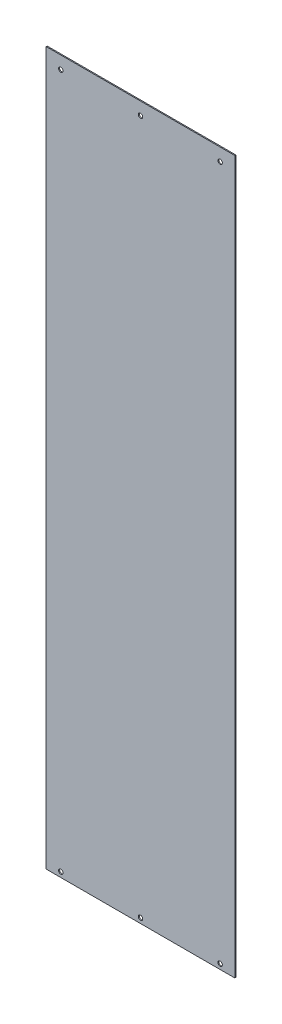
SolidWorks part; units mm, degrees
ref_plane "Front" through (0, 0, 0) normal (0, 0, 1) x (1, 0, 0)
ref_plane "Top" through (0, 0, 0) normal (0, 1, 0) x (1, 0, 0)
ref_plane "Right" through (0, 0, 0) normal (1, 0, 0) x (0, 0, -1)
sketch "Sketch1" plane through (0, 0, 0) normal (0, 0, 1) x (1, 0, 0)
  line L0 (0, -21.6138) -> (0, 1175.9168) construction
  line L1 (-148, 0) -> (148, 0)
  line L2 (-148, 0) -> (-148, 1118)
  line L3 (-148, 1118) -> (148, 1118)
  line L4 (148, 0) -> (148, 1118)
  dimension "D1" = 296
  dimension "D2" = 1118
extrude "Boss-Extrude1" add sketch "Sketch1" along normal blind 1.6
hole_wizard "Ø7.0 (7) Diameter Hole1" positions "Sketch3" profile "Sketch2" hole size "Ø7.0" standard "JIS" end condition through all
sketch "Sketch3" plane through (0, 0, 1.6) normal (0, 0, 1) x (1, 0, 0)
  line L0 (0, -32.1709) -> (0, 1176.6164) construction
  line L2 (-148, 0) -> (148, 0) construction
  point P0 (-125, 8)
  point P1 (0, 8)
  point P3 (125, 8)
  dimension "D1" = 250
  dimension "D2" = 8
sketch "Sketch2" plane through (-125, 8, 1.6) normal (1, 0, 0) x (0, -1, 0)
  line L0 (0, 0) -> (0, 1.6)
  line L1 (0, 1.6) -> (3.5, 1.6)
  line L2 (3.5, 1.6) -> (3.5, 0)
  line L5 (3.5, 0) -> (0, 0)
  line L11 (0, -6.35) -> (0, 107.95) construction
  dimension "Thru Hole Dia." = 7
  dimension "Thru Hole Depth" = 1.6
pattern_linear "LPattern1" count 2 spacing 1090 along (0, 1, 0) of "Ø7.0 (7) Diameter Hole1"
